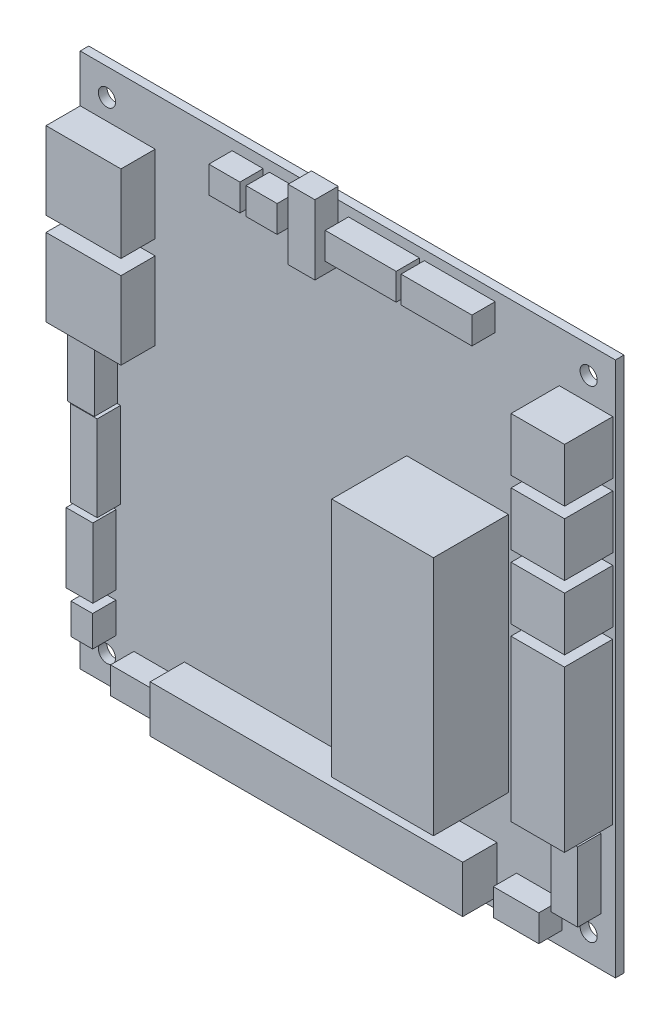
SolidWorks part; units mm, degrees
ref_plane "前视基准面" through (0, 0, 0) normal (0, 0, 1) x (1, 0, 0)
ref_plane "上视基准面" through (0, 0, 0) normal (0, 1, 0) x (1, 0, 0)
ref_plane "右视基准面" through (0, 0, 0) normal (1, 0, 0) x (0, 0, -1)
other "Configuration Table"
sketch "草图1" plane through (0, 0, 0) normal (0, 0, 1) x (1, 0, 0)
  line L1 (-50, 32) -> (50, 32)
  line L2 (-50, 32) -> (-50, 132)
  line L3 (-50, 132) -> (50, 132)
  line L4 (50, 32) -> (50, 132)
  circle A0 centre (-45, 37) radius 1.6
  circle A1 centre (45, 37) radius 1.6
  circle A2 centre (45, 127) radius 1.6
  circle A3 centre (-45, 127) radius 1.6
extrude "100x100_rotated_J101_rear_J801_front" add sketch "草图1" along normal blind 1.6 from offset 25
sketch "草图2" plane through (0, 0, 0) normal (0, 0, 1) x (1, 0, 0)
  line L1 (39.5045, 112.5895) -> (49.5045, 112.5895)
  line L2 (39.5045, 112.5895) -> (39.5045, 122.5895)
  line L3 (39.5045, 122.5895) -> (49.5045, 122.5895)
  line L4 (49.5045, 112.5895) -> (49.5045, 122.5895)
extrude "J102_connector_envelope_rotated" add sketch "草图2" along normal blind 9 from offset 26.6
sketch "草图3" plane through (0, 0, 0) normal (0, 0, 1) x (1, 0, 0)
  line L1 (-49.9835, 108.621) -> (-35.9835, 108.621)
  line L2 (-49.9835, 108.621) -> (-49.9835, 123.121)
  line L3 (-49.9835, 123.121) -> (-35.9835, 123.121)
  line L4 (-35.9835, 108.621) -> (-35.9835, 123.121)
extrude "J201_connector_envelope_rotated" add sketch "草图3" along normal blind 6.4 from offset 26.6
sketch "草图4" plane through (0, 0, 0) normal (0, 0, 1) x (1, 0, 0)
  line L1 (-49.9835, 91.349) -> (-35.9835, 91.349)
  line L2 (-49.9835, 91.349) -> (-49.9835, 105.849)
  line L3 (-49.9835, 105.849) -> (-35.9835, 105.849)
  line L4 (-35.9835, 91.349) -> (-35.9835, 105.849)
extrude "J501_connector_envelope_rotated" add sketch "草图4" along normal blind 6.4 from offset 26.6
sketch "草图5" plane through (0, 0, 0) normal (0, 0, 1) x (1, 0, 0)
  line L1 (39.5045, 88.5225) -> (49.5045, 88.5225)
  line L2 (39.5045, 88.5225) -> (39.5045, 98.5225)
  line L3 (39.5045, 98.5225) -> (49.5045, 98.5225)
  line L4 (49.5045, 88.5225) -> (49.5045, 98.5225)
extrude "J301_connector_envelope_rotated" add sketch "草图5" along normal blind 9 from offset 26.6
sketch "草图6" plane through (0, 0, 0) normal (0, 0, 1) x (1, 0, 0)
  line L1 (39.5045, 100.5555) -> (49.5045, 100.5555)
  line L2 (39.5045, 100.5555) -> (39.5045, 110.5555)
  line L3 (39.5045, 110.5555) -> (49.5045, 110.5555)
  line L4 (49.5045, 100.5555) -> (49.5045, 110.5555)
extrude "J304_connector_envelope_rotated" add sketch "草图6" along normal blind 9 from offset 26.6
sketch "草图7" plane through (0, 0, 0) normal (0, 0, 1) x (1, 0, 0)
  line L1 (39.4745, 56.5485) -> (49.4745, 56.5485)
  line L2 (39.4745, 56.5485) -> (39.4745, 86.5485)
  line L3 (39.4745, 86.5485) -> (49.4745, 86.5485)
  line L4 (49.4745, 56.5485) -> (49.4745, 86.5485)
extrude "J302_connector_envelope_rotated" add sketch "草图7" along normal blind 9 from offset 26.6
sketch "草图8" plane through (0, 0, 0) normal (0, 0, 1) x (1, 0, 0)
  line L1 (-21.6075, 125.055) -> (-15.8075, 125.055)
  line L2 (-21.6075, 125.055) -> (-21.6075, 130.055)
  line L3 (-21.6075, 130.055) -> (-15.8075, 130.055)
  line L4 (-15.8075, 125.055) -> (-15.8075, 130.055)
extrude "J305_connector_envelope_rotated" add sketch "草图8" along normal blind 4.35 from offset 26.6
sketch "草图9" plane through (0, 0, 0) normal (0, 0, 1) x (1, 0, 0)
  line L1 (-14.6545, 125.055) -> (-8.8545, 125.055)
  line L2 (-14.6545, 125.055) -> (-14.6545, 130.055)
  line L3 (-14.6545, 130.055) -> (-8.8545, 130.055)
  line L4 (-8.8545, 125.055) -> (-8.8545, 130.055)
extrude "J306_connector_envelope_rotated" add sketch "草图9" along normal blind 4.35 from offset 26.6
sketch "草图10" plane through (0, 0, 0) normal (0, 0, 1) x (1, 0, 0)
  line L1 (42.2985, 41.0445) -> (47.2985, 41.0445)
  line L2 (42.2985, 41.0445) -> (42.2985, 54.0445)
  line L3 (42.2985, 54.0445) -> (47.2985, 54.0445)
  line L4 (47.2985, 41.0445) -> (47.2985, 54.0445)
extrude "J401_connector_envelope_rotated" add sketch "草图10" along normal blind 4.35 from offset 26.6
sketch "草图11" plane through (0, 0, 0) normal (0, 0, 1) x (1, 0, 0)
  line L1 (-47.472, 62.4055) -> (-42.472, 62.4055)
  line L2 (-47.472, 62.4055) -> (-47.472, 78.4055)
  line L3 (-47.472, 78.4055) -> (-42.472, 78.4055)
  line L4 (-42.472, 62.4055) -> (-42.472, 78.4055)
extrude "J502_connector_envelope_rotated" add sketch "草图11" along normal blind 4.35 from offset 26.6
sketch "草图12" plane through (0, 0, 0) normal (0, 0, 1) x (1, 0, 0)
  line L1 (-47.853, 37.1075) -> (-42.853, 37.1075)
  line L2 (-47.853, 37.1075) -> (-47.853, 50.1075)
  line L3 (-47.853, 50.1075) -> (-42.853, 50.1075)
  line L4 (-42.853, 37.1075) -> (-42.853, 50.1075)
sketch "草图13" plane through (0, 0, 0) normal (0, 0, 1) x (1, 0, 0)
  line L1 (-48.285, 48.1575) -> (-43.285, 48.1575)
  line L2 (-48.285, 48.1575) -> (-48.285, 61.1575)
  line L3 (-48.285, 61.1575) -> (-43.285, 61.1575)
  line L4 (-43.285, 48.1575) -> (-43.285, 61.1575)
extrude "J602_connector_envelope_rotated" add sketch "草图13" along normal blind 4.35 from offset 26.6
sketch "草图14" plane through (0, 0, 0) normal (0, 0, 1) x (1, 0, 0)
  line L1 (-48.006, 78.5105) -> (-43.006, 78.5105)
  line L2 (-48.006, 78.5105) -> (-48.006, 91.5105)
  line L3 (-48.006, 91.5105) -> (-43.006, 91.5105)
  line L4 (-43.006, 78.5105) -> (-43.006, 91.5105)
extrude "J701_connector_envelope_rotated" add sketch "草图14" along normal blind 4.35 from offset 26.6
sketch "草图15" plane through (0, 0, 0) normal (0, 0, 1) x (1, 0, 0)
  line L1 (0.1345, 125.209) -> (13.3845, 125.209)
  line L2 (0.1345, 125.209) -> (0.1345, 130.209)
  line L3 (0.1345, 130.209) -> (13.3845, 130.209)
  line L4 (13.3845, 125.209) -> (13.3845, 130.209)
extrude "J702_connector_envelope_rotated" add sketch "草图15" along normal blind 4.35 from offset 26.6
sketch "草图16" plane through (0, 0, 0) normal (0, 0, 1) x (1, 0, 0)
  line L1 (14.2925, 125.209) -> (27.5425, 125.209)
  line L2 (14.2925, 125.209) -> (14.2925, 130.209)
  line L3 (14.2925, 130.209) -> (27.5425, 130.209)
  line L4 (27.5425, 125.209) -> (27.5425, 130.209)
extrude "J703_connector_envelope_rotated" add sketch "草图16" along normal blind 4.35 from offset 26.6
sketch "草图17" plane through (0, 0, 0) normal (0, 0, 1) x (1, 0, 0)
  line L1 (-39.9695, 34.859) -> (-31.4695, 34.859)
  line L2 (-39.9695, 34.859) -> (-39.9695, 39.859)
  line L3 (-39.9695, 39.859) -> (-31.4695, 39.859)
  line L4 (-31.4695, 34.859) -> (-31.4695, 39.859)
extrude "J704_connector_envelope_rotated" add sketch "草图17" along normal blind 4.35 from offset 26.6
sketch "草图18" plane through (0, 0, 0) normal (0, 0, 1) x (1, 0, 0)
  line L1 (-6.8005, 121.204) -> (-1.8005, 121.204)
  line L2 (-6.8005, 121.204) -> (-6.8005, 134.204)
  line L3 (-6.8005, 134.204) -> (-1.8005, 134.204)
  line L4 (-1.8005, 121.204) -> (-1.8005, 134.204)
extrude "J705_connector_envelope_rotated" add sketch "草图18" along normal blind 4.35 from offset 26.6
sketch "草图19" plane through (0, 0, 0) normal (0, 0, 1) x (1, 0, 0)
  line L1 (31.5315, 34.732) -> (40.0315, 34.732)
  line L2 (31.5315, 34.732) -> (31.5315, 39.732)
  line L3 (31.5315, 39.732) -> (40.0315, 39.732)
  line L4 (40.0315, 34.732) -> (40.0315, 39.732)
extrude "J706_connector_envelope_rotated" add sketch "草图19" along normal blind 4.35 from offset 26.6
sketch "草图20" plane through (0, 0, 0) normal (0, 0, 1) x (1, 0, 0)
  line L1 (-30.525, 34.066) -> (27.875, 34.066)
  line L2 (-30.525, 34.066) -> (-30.525, 42.866)
  line L3 (-30.525, 42.866) -> (27.875, 42.866)
  line L4 (27.875, 34.066) -> (27.875, 42.866)
extrude "J801_connector_envelope_rotated" add sketch "草图20" along normal blind 6.4 from offset 26.6
sketch "草图21" plane through (0, 0, 0) normal (0, 0, 1) x (1, 0, 0)
  line L1 (11, 52) -> (30, 52)
  line L2 (11, 52) -> (11, 97)
  line L3 (11, 97) -> (30, 97)
  line L4 (30, 52) -> (30, 97)
extrude "Nano_socket" add sketch "草图21" along normal blind 12.4 from offset 26.6
sketch "草图22" plane through (0, 0, 0) normal (0, 0, 1) x (1, 0, 0)
  line L1 (11, 52) -> (30, 52)
  line L2 (11, 52) -> (11, 97)
  line L3 (11, 97) -> (30, 97)
  line L4 (30, 52) -> (30, 97)
extrude "Nano_PCB" add sketch "草图22" along normal blind 1.6 from offset 39
sketch "草图23" plane through (0, 0, 0) normal (0, 0, 1) x (1, 0, 0)
  line L1 (-47.378, 40.7325) -> (-43.328, 40.7325)
  line L2 (-47.378, 40.7325) -> (-47.378, 46.4825)
  line L3 (-47.378, 46.4825) -> (-43.328, 46.4825)
  line L4 (-43.328, 40.7325) -> (-43.328, 46.4825)
extrude "J601_GH2P_corrected_body_reference" add sketch "草图23" along normal blind 4.35 from offset 26.6
